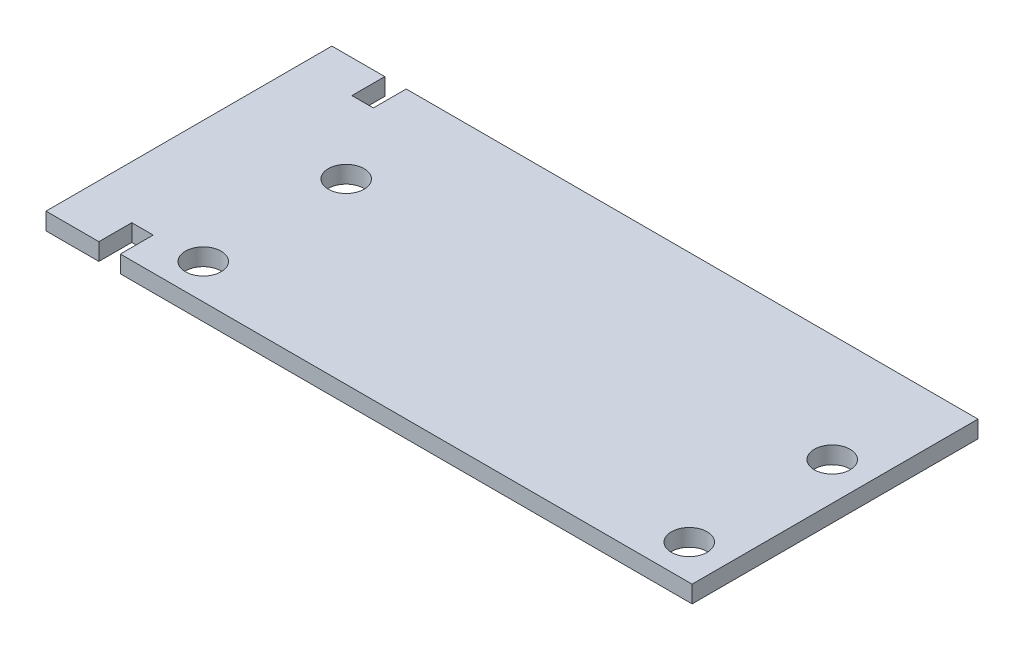
SolidWorks part; units mm, degrees
ref_plane "Front" through (0, 0, 0) normal (0, 0, 1) x (1, 0, 0)
ref_plane "Top" through (0, 0, 0) normal (0, 1, 0) x (1, 0, 0)
ref_plane "Right" through (0, 0, 0) normal (1, 0, 0) x (0, 0, -1)
sketch "Sketch1" plane through (0, 0, 0) normal (0, 1, 0) x (1, 0, 0)
  line L0 (0, 17.7) -> (-1.5, 17.7)
  line L1 (0, 0) -> (40, 0)
  line L3 (0, 20) -> (40, 20)
  line L4 (40, 0) -> (40, 20)
  line L5 (-1.5, 17.7) -> (-1.5, 20)
  line L6 (-1.5, 20) -> (-5.2, 20)
  line L7 (-5.2, 20) -> (-5.2, 0)
  line L8 (-5.2, 0) -> (-1.5, 0)
  line L9 (-1.5, 0) -> (-1.5, 2.3)
  line L10 (-1.5, 2.3) -> (0, 2.3)
  line L11 (0, 0) -> (0, 2.3)
  line L12 (0, 17.7) -> (0, 20)
  line L13 (0, 17.7) -> (0, 2.3) construction
  dimension "D1" = 40
  dimension "D2" = 20
  dimension "D3" = 5.2
  dimension "D4" = 15.4
  dimension "D5" = 1.5
extrude "Boss-Extrude1" add sketch "Sketch1" along normal blind 1.2
sketch "Sketch2" plane through (0, 1.2, 0) normal (0, 1, 0) x (1, 0, 0)
  line L0 (3.35, 2.45) -> (3.35, 12.45) construction
  line L1 (3.35, 12.45) -> (37.35, 12.45) construction
  line L2 (37.35, 12.45) -> (37.35, 2.45) construction
  line L3 (37.35, 2.45) -> (3.35, 2.45) construction
  line L4 (40, 0) -> (40, 20) construction
  line L5 (0, 0) -> (40, 0) construction
  circle A0 centre (37.35, 2.45) radius 1.25
  circle A1 centre (37.35, 12.45) radius 1.25
  circle A2 centre (3.35, 12.45) radius 1.25
  circle A3 centre (3.35, 2.45) radius 1.25
  dimension "D3" = 2.5
  dimension "D4" = 2.65
  dimension "D1" = 34
  dimension "D2" = 10
  dimension "D5" = 2.45
extrude "Cut-Extrude1" cut sketch "Sketch2" against normal through all
